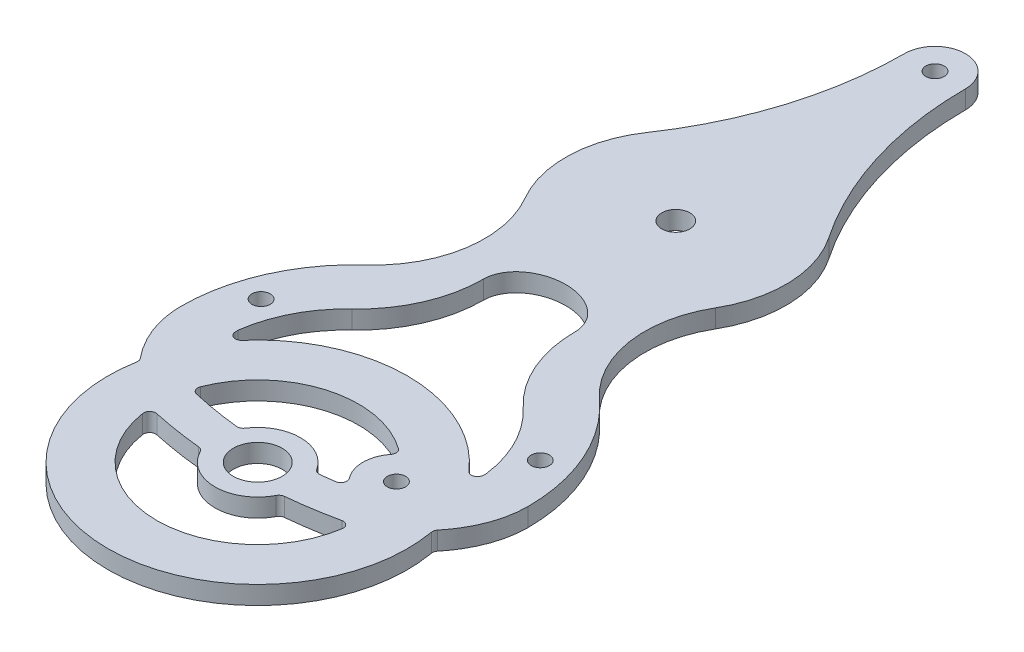
SolidWorks part; units mm, degrees
ref_plane "Front Plane" through (0, 0, 0) normal (0, 0, 1) x (1, 0, 0)
ref_plane "Top Plane" through (0, 0, 0) normal (0, 1, 0) x (1, 0, 0)
ref_plane "Right Plane" through (0, 0, 0) normal (1, 0, 0) x (0, 0, -1)
sketch "Sketch1" plane through (0, 0, 0) normal (0, 1, 0) x (1, 0, 0)
  line L1 (0, -52.0078) -> (0, -64.2302) construction
  circle A8 centre (0, -68.5564) radius 24.5485
  circle A9 centre (0, -68.5564) radius 8.2743 construction
  circle A10 centre (0, -68.5564) radius 16.5485
  ellipse E0 centre (0, -51.4173) end of major axis (20.3628, -51.4173) minor radius 12.813 construction
  point P0 (0, -52.0078)
  point P1 (0, -44.0078)
  dimension "D2" = 49.0971
  dimension "D3" = 33.0971
  dimension "D1" = 8
extrude "Boss-Extrude1" add sketch "Sketch1" along normal blind 3
sketch "Sketch2" plane through (0, 0, 0) normal (0, -1, 0) x (1, 0, 0)
  line L0 (0, 71.5564) -> (0, 65.5564) construction
  line L5 (-24.5125, 67.2269) -> (-23.4288, 61.2269)
  line L6 (24.5125, 67.2269) -> (23.4288, 61.2269)
  circle A1 centre (0, 0) radius 68.5564 construction
  arc A2 (-24.5125, 67.2269) -> (24.5125, 67.2269) centre (0, 0) cw
  arc A3 (-23.4288, 61.2269) -> (23.4288, 61.2269) centre (0, 0) cw
  circle A4 centre (0, 68.5564) radius 24.5485 construction
  point P10 (0, 68.5564)
  dimension "D1" = 6
extrude "Boss-Extrude2" add sketch "Sketch2" against normal up to surface (3 mm away) up to face at (0, 3, 93.1049)
sketch "Sketch4" plane through (0, 0, 0) normal (0, -1, 0) x (1, 0, 0)
  arc A1 (11.2067, 64.5914) -> (10.512, 55.7754) centre (14.1202, 59.9265) ccw
  arc A2 (10.512, 55.7754) -> (15.7966, 63.6247) centre (0, 68.5564) ccw
  circle A3 centre (14.1202, 59.9265) radius 5.5 construction
  circle A4 centre (0, 68.5564) radius 16.5485 construction
  circle A6 centre (0, 68.5564) radius 7
  arc A7 (23.4288, 61.2269) -> (-23.4288, 61.2269) centre (0, 0) ccw construction
  arc A8 (11.2067, 64.5914) -> (15.7966, 63.6247) centre (0, 0) cw
  dimension "D2" = 14
extrude "Boss-Extrude3" add sketch "Sketch4" against normal up to surface (3 mm away) up to face at (0, 3, 93.1049)
fillet "Fillet1" radius 1 9 edges at (10.512, 1.5, 55.7754) (16.514, 1.5, 69.6247) (-16.514, 1.5, 69.6247) (-6.4549, 1.5, 71.2647) (6.4549, 1.5, 71.2647) (-15.7966, 1.5, 63.6247) (-6.1777, 1.5, 65.2647) (6.1777, 1.5, 65.2647) (11.2067, 1.5, 64.5914)
sketch "Sketch5" plane through (0, 3, 0) normal (0, 1, 0) x (1, 0, 0)
  circle A0 centre (0, -68.5564) radius 4
  circle A1 centre (14.1202, -59.9265) radius 1.5
  circle A2 centre (0, -68.5564) radius 7 construction
  arc A3 (10.512, -55.7754) -> (11.2067, -64.5914) centre (14.1202, -59.9265) ccw construction
  circle A4 centre (14.1202, -59.9265) radius 1.5 construction
  dimension "D2" = 8
extrude "Cut-Extrude1" cut sketch "Sketch5" against normal through all
sketch "Sketch6" plane through (0, 0, 0) normal (0, -1, 0) x (1, 0, 0)
  line L0 (0, -1000) -> (0, 49000) construction
  circle A0 centre (0, 68.5564) radius 24.5485 construction
  arc A1 (-28.4436, 52.6898) -> (-19.0837, 31.5984) centre (0, 52.6898) ccw construction
  arc A2 (-28.4436, 52.6898) -> (-19.0837, 31.5984) centre (0, 52.6898) ccw
  arc A3 (-15.6012, 9.1024) -> (-19.0837, 31.5984) centre (-31.2024, 18.2047) ccw construction
  arc A4 (-15.6012, 9.1024) -> (-19.0837, 31.5984) centre (-31.2024, 18.2047) ccw
  arc A5 (-24.0821, 63.7936) -> (-19.8886, 54.1663) centre (0, 68.5564) ccw
  arc A6 (-20.3628, 51.4173) -> (-14.017, 39.0376) centre (0.0568, 54.0679) ccw
  arc A7 (-14.017, 39.0376) -> (-7.5, 24.0072) centre (-28.0909, 24.0072) cw
  circle A8 centre (-22.8961, 45.1123) radius 1.5
  circle A9 centre (-22.8961, 45.1123) radius 1.5 construction
  arc A10 (-5, -42.4971) -> (5, -42.4971) centre (0, -42.4971) ccw construction
  arc A11 (-5, -42.4971) -> (-14.944, -10.1452) centre (-62.5986, -42.4971) ccw construction
  arc A12 (-15.6012, 9.1024) -> (-14.944, -10.1452) centre (0, 0) ccw construction
  arc A13 (-5, -42.4971) -> (5, -42.4971) centre (0, -42.4971) ccw
  arc A14 (-5, -42.4971) -> (-14.944, -10.1452) centre (-62.5986, -42.4971) ccw
  arc A15 (-15.6012, 9.1024) -> (-14.944, -10.1452) centre (0, 0) ccw
  circle A16 centre (0, -42.4971) radius 1.5 construction
  circle A17 centre (0, -42.4971) radius 1.5
  circle A18 centre (0, 0) radius 2.3 construction
  circle A19 centre (0, 0) radius 2.3
  circle A20 centre (22.8961, 45.1123) radius 1.5
  arc A21 (20.3628, 51.4173) -> (14.017, 39.0376) centre (-0.0568, 54.0679) cw
  arc A22 (14.017, 39.0376) -> (7.5, 24.0072) centre (28.0909, 24.0072) ccw
  arc A23 (5, -42.4971) -> (14.944, -10.1452) centre (62.5986, -42.4971) cw
  arc A24 (15.6012, 9.1024) -> (14.944, -10.1452) centre (0, 0) cw
  arc A25 (15.6012, 9.1024) -> (19.0837, 31.5984) centre (31.2024, 18.2047) cw
  arc A26 (28.4436, 52.6898) -> (19.0837, 31.5984) centre (0, 52.6898) cw
  arc A27 (24.0821, 63.7936) -> (19.8886, 54.1663) centre (0, 68.5564) cw
  ellipse E0 centre (0, 52.6898) end of major axis (28.4436, 52.6898) minor radius 20.8666 (-24.0821, 63.7936) -> (-28.4436, 52.6898) ccw
  ellipse E1 centre (0, 51.4173) end of major axis (-20.3628, 51.4173) minor radius 12.813 (19.8886, 54.1663) -> (20.3628, 51.4173) cw
  ellipse E2 centre (0, 52.6898) end of major axis (-28.4436, 52.6898) minor radius 20.8666 (28.4436, 52.6898) -> (-28.4436, 52.6898) ccw construction
  ellipse E3 centre (0, 51.4173) end of major axis (20.3628, 51.4173) minor radius 12.813 (-19.8886, 54.1663) -> (-20.3628, 51.4173) ccw
  ellipse E4 centre (0, 52.6898) end of major axis (-28.4436, 52.6898) minor radius 20.8666 (24.0821, 63.7936) -> (28.4436, 52.6898) cw
  ellipse E5 centre (0, 24.0072) end of major axis (-7.5, 24.0072) minor radius 5.9448 (7.5, 24.0072) -> (-7.5, 24.0072) cw
  point P31 (0, 18.0624)
extrude "Boss-Extrude4" add sketch "Sketch6" against normal up to surface (3 mm away) up to face at (0, 3, 72.5564)
fillet "Fillet2" radius 1 4 edges at (19.8886, 1.5, 54.1663) (-19.8886, 1.5, 54.1663) (24.0821, 1.5, 63.7936) (-24.0821, 1.5, 63.7936)
sketch "Sketch7" plane through (0, 3, 0) normal (0, 1, 0) x (1, 0, 0)
  line L0 (-1.5, -11.1916) -> (-1.5, -5.7827) construction
  line L2 (-4.258, -4.1904) -> (-8.9422, -6.8948) construction
  line L4 (-4.258, -4.1904) -> (-8.9422, -6.8948)
  line L5 (-1.5, -11.1916) -> (-1.5, -5.7827)
  arc A2 (-5.6192, -13.975) -> (-1.5, -11.1916) centre (-4.5, -11.1916) ccw construction
  arc A5 (-8.9422, -6.8948) -> (-9.2931, -11.8539) centre (-7.4422, -9.4929) ccw construction
  arc A6 (-9.2931, -11.8539) -> (-5.6192, -13.975) centre (0, 0) ccw construction
  arc A7 (-8.9422, -6.8948) -> (-9.2931, -11.8539) centre (-7.4422, -9.4929) ccw
  arc A8 (-9.2931, -11.8539) -> (-5.6192, -13.975) centre (0, 0) ccw
  arc A9 (-5.6192, -13.975) -> (-1.5, -11.1916) centre (-4.5, -11.1916) ccw
  arc A10 (-3.1615, -4.2538) -> (-4.258, -4.1904) centre (-3.758, -5.0564) ccw construction
  arc A11 (-3.1615, -4.2538) -> (-2.1032, -4.8648) centre (0, 0) ccw construction
  arc A12 (-1.5, -5.7827) -> (-2.1032, -4.8648) centre (-2.5, -5.7827) ccw construction
  arc A13 (-3.1615, -4.2538) -> (-4.258, -4.1904) centre (-3.758, -5.0564) ccw
  arc A14 (-3.1615, -4.2538) -> (-2.1032, -4.8648) centre (0, 0) ccw
  arc A15 (-1.5, -5.7827) -> (-2.1032, -4.8648) centre (-2.5, -5.7827) ccw
extrude "Cut-Extrude2" [suppressed] cut sketch "Sketch7" against normal through all
pattern_circular "CirPattern1" [suppressed] count 6 over 360
